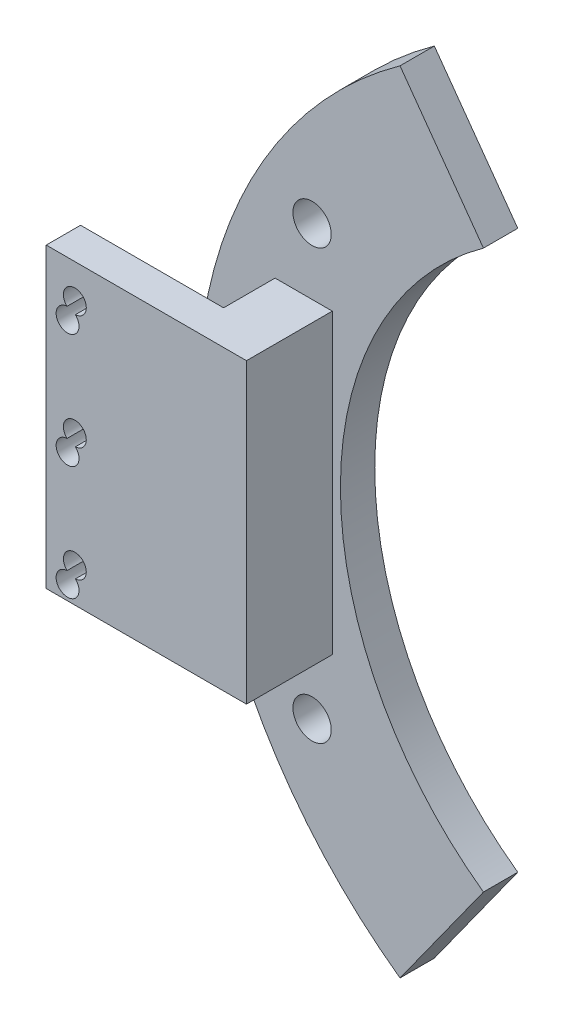
SolidWorks part; units mm, degrees
material "PEI"
ref_plane "前视基准面" through (0, 0, 0) normal (0, 0, 1) x (1, 0, 0)
ref_plane "上视基准面" through (0, 0, 0) normal (0, 1, 0) x (1, 0, 0)
ref_plane "右视基准面" through (0, 0, 0) normal (1, 0, 0) x (0, 0, -1)
other "Configuration Table"
sketch "草图1" plane through (0, 0, 0) normal (0, 0, 1) x (1, 0, 0)
  circle A0 centre (0, 0) radius 85
  circle A1 centre (0, 0) radius 60
  dimension "D1" = 170
  dimension "D2" = 120
extrude "凸台-拉伸1" add sketch "草图1" along normal blind 6
sketch "草图2" plane through (0, 0, 6) normal (0, 0, 1) x (1, 0, 0)
  line L0 (0, 0) -> (0, 90.5173) construction
  line L1 (0, 0) -> (-91.1914, 52.6494) construction
  line L2 (0, 0) -> (-88.371, -51.021) construction
  line L3 (0, 0) -> (0, -97.4369) construction
  line L4 (0, 0) -> (91.1914, 52.6494) construction
  line L5 (0, 0) -> (88.371, -51.021) construction
  circle A0 centre (0, 75) radius 3.35
  circle A1 centre (64.9519, 37.5) radius 3.35
  circle A2 centre (64.9519, -37.5) radius 3.35
  circle A3 centre (0, -75) radius 3.35
  circle A4 centre (-64.9519, -37.5) radius 3.35
  circle A5 centre (-64.9519, 37.5) radius 3.35
  dimension "D1" = 6.7
  dimension "D8" = 6.7
  dimension "D9" = 6.7
  dimension "D10" = 6.7
  dimension "D2" = 75
  dimension "D3" = 60
  dimension "D4" = 60
  dimension "D5" = 75
  dimension "D6" = 75
  dimension "D7" = 75
extrude "切除-拉伸1" cut sketch "草图2" against normal blind 10
sketch "草图3" plane through (0, 0, 6) normal (0, 0, 1) x (1, 0, 0)
  line L0 (0, 0) -> (-135.1725, 0) construction
  line L5 (0, 0) -> (0, 80.8621) construction
  line L11 (71.4195, -26.0097) -> (61.4195, -26.0097)
  line L12 (-71.4195, 25.9903) -> (-61.4195, 25.9903)
  line L16 (-71.4195, 25.9903) -> (-71.4195, -26.0097)
  line L17 (-71.4195, -26.0097) -> (-61.4195, -26.0097)
  line L18 (-61.4195, 25.9903) -> (-61.4195, -26.0097)
  line L19 (71.4195, 25.9903) -> (71.4195, -26.0097)
  line L20 (71.4195, 25.9903) -> (61.4195, 25.9903)
  line L21 (61.4195, 25.9903) -> (61.4195, -26.0097)
  point P2 (-71.4195, 0)
  dimension "D1" = 10
  dimension "D2" = 52
extrude "凸台-拉伸2" add sketch "草图3" along normal blind 15
sketch "草图8" plane through (-71.4195, 0, 0) normal (-1, 0, 0) x (0, 0, 1)
  line L0 (21, -26.0097) -> (6, -26.0097) construction
  line L1 (21, 25.9903) -> (15, 25.9903)
  line L2 (21, 25.9903) -> (21, -26.0097)
  line L3 (21, -26.0097) -> (15, -26.0097)
  line L4 (15, 25.9903) -> (15, -26.0097)
  dimension "D1" = 6
extrude "凸台-拉伸3" add sketch "草图8" along normal blind 25
sketch "草图10" plane through (71.4195, 0, 0) normal (1, 0, 0) x (0, 0, -1)
  line L0 (-21, -26.0097) -> (-6, -26.0097) construction
  line L1 (-21, 25.9903) -> (-12.9967, 25.9903)
  line L2 (-21, 25.9903) -> (-21, -26.0097)
  line L3 (-21, -26.0097) -> (-12.9967, -26.0097)
  line L4 (-12.9967, 25.9903) -> (-12.9967, -26.0097)
  dimension "D1" = 8.0033
extrude "凸台-拉伸4" add sketch "草图10" along normal blind 25
sketch "草图11" plane through (0, 0, 21) normal (0, 0, 1) x (1, 0, 0)
  line L0 (-96.4195, -26.0097) -> (-96.4195, 25.9903) construction
  line L1 (0, 0) -> (0, 29.3779) construction
  line L2 (0, 0) -> (27.769, 0) construction
  circle A0 centre (-91.4195, 0) radius 2
  circle A1 centre (-91.4195, 20) radius 2
  circle A2 centre (91.4195, 0) radius 2
  circle A3 centre (91.4195, 20) radius 2
  circle A4 centre (91.4195, -20) radius 2
  circle A5 centre (-91.4195, -20) radius 2
  dimension "D1" = 5
  dimension "D2" = 20
extrude "切除-拉伸3" cut sketch "草图11" against normal blind 25
sketch "草图12" plane through (0, 0, 6) normal (0, 0, 1) x (1, 0, 0)
  line L0 (-35, 48.734) -> (-49.5833, 69.0398)
  line L1 (-35, 90) -> (35, 90)
  line L2 (-35, 90) -> (-35, 77.4597)
  line L3 (-35, -90) -> (35, -90)
  line L5 (-35, 90) -> (35, -90) construction
  line L6 (-35, -90) -> (35, 90) construction
  line L7 (-35, -48.734) -> (-49.5833, -69.0398)
  line L8 (-35, 48.734) -> (-35, -48.734)
  line L9 (-35, -77.4597) -> (-35, -90)
  line L11 (35, 90) -> (153.5248, 90)
  line L13 (35, -90) -> (153.5248, -90)
  line L14 (153.5248, 90) -> (153.5248, -90)
  circle A0 centre (0, 0) radius 60 construction
  circle A1 centre (0, 0) radius 85 construction
  arc A2 (-49.5833, -69.0398) -> (-35, -77.4597) centre (0, 0) ccw
  arc A5 (-35, 77.4597) -> (-49.5833, 69.0398) centre (0, 0) ccw
  point P0 (0, 0)
  dimension "D1" = 70
  dimension "D2" = 180
extrude "切除-拉伸4" cut sketch "草图12" against normal mid plane 100
sketch "草图6" plane through (0, 0, 26) normal (0, 0, 1) x (1, 0, 0)
  line L0 (0, 0) -> (0, 48.6782) construction
  line L1 (92.6897, -3.4598) -> (92.6897, -43.4598) construction
  line L2 (92.6897, -3.4598) -> (92.6897, 36.5402) construction
  circle A0 centre (92.6897, -3.4598) radius 2
  circle A1 centre (92.6897, -23.4598) radius 2
  circle A2 centre (92.6897, 16.5402) radius 2
  circle A3 centre (-92.6897, -23.4598) radius 2
  circle A4 centre (-92.6897, -3.4598) radius 2
  circle A5 centre (-92.6897, 16.5402) radius 2
  dimension "D1" = 4
  dimension "D2" = 20
  dimension "D4" = 4
  dimension "D5" = 4
  dimension "D3" = 20
extrude "切除-拉伸2" cut sketch "草图6" against normal blind 20
